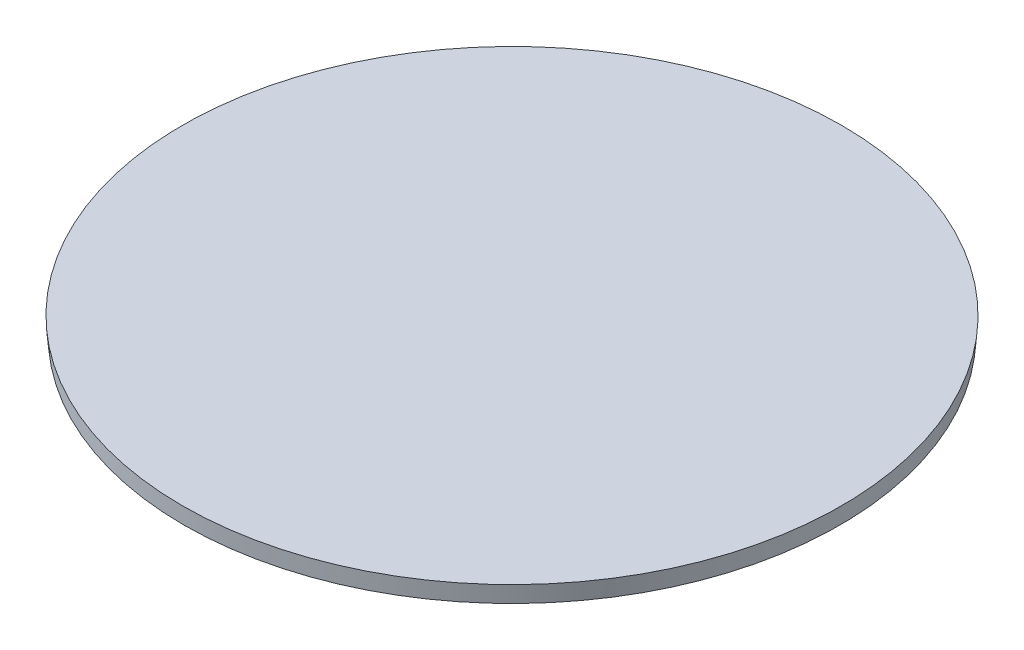
SolidWorks part; units mm, degrees
ref_plane "Front Plane" through (0, 0, 0) normal (0, 0, 1) x (1, 0, 0)
ref_plane "Top Plane" through (0, 0, 0) normal (0, 1, 0) x (1, 0, 0)
ref_plane "Right Plane" through (0, 0, 0) normal (1, 0, 0) x (0, 0, -1)
sketch "Sketch1" plane through (0, 0, 0) normal (0, 1, 0) x (1, 0, 0)
  circle A0 centre (0, 0) radius 18.85
  dimension "D1" = 37.7
extrude "Extrude1" add sketch "Sketch1" against normal blind 1 draft 5
